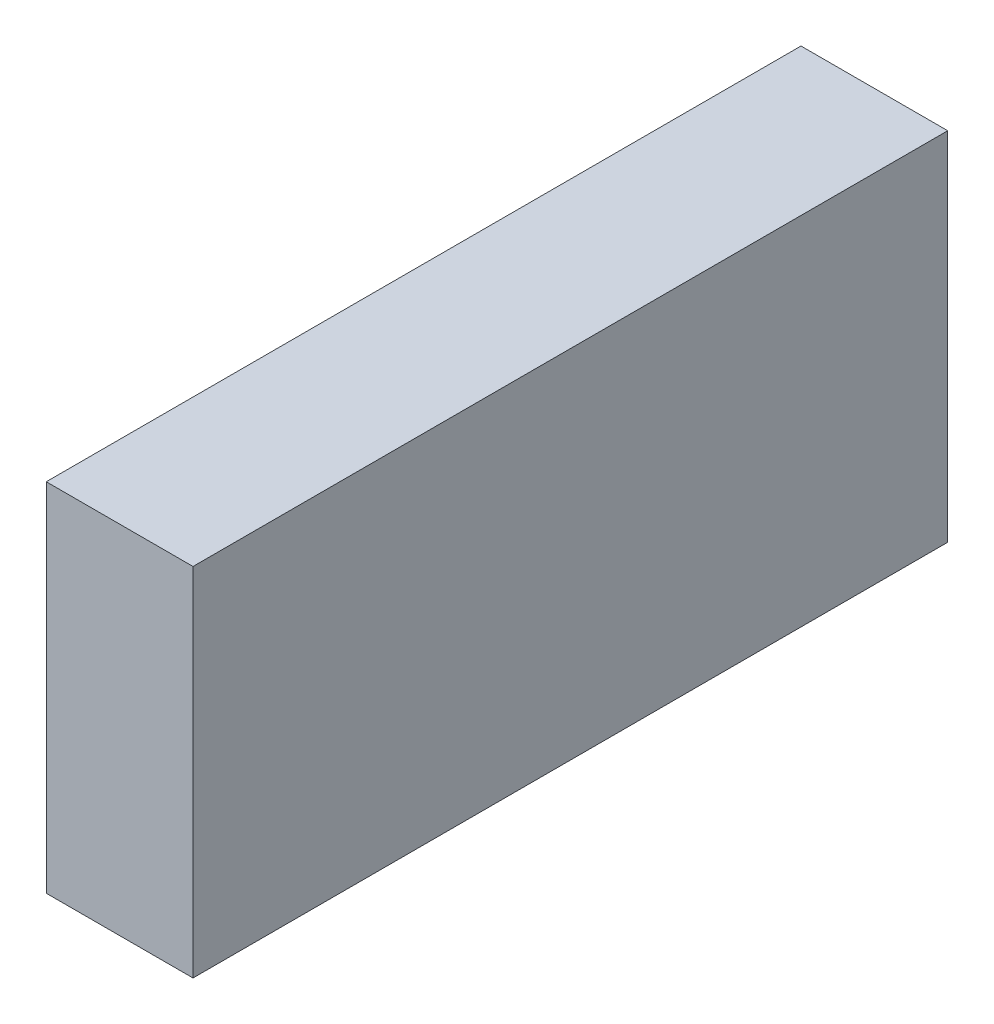
SolidWorks part; units mm, degrees
ref_plane "Front Plane" through (0, 0, 0) normal (0, 0, 1) x (1, 0, 0)
ref_plane "Top Plane" through (0, 0, 0) normal (0, 1, 0) x (1, 0, 0)
ref_plane "Right Plane" through (0, 0, 0) normal (1, 0, 0) x (0, 0, -1)
sketch "Sketch1" plane through (0, 0, 0) normal (1, 0, 0) x (0, 0, -1)
  line L0 (0, 30.4888) -> (0, -39.691) construction
  line L1 (-52.382, 0) -> (46.1124, 0) construction
  line L3 (36, -17) -> (-36, -17)
  line L4 (36, -17) -> (36, 17)
  line L5 (36, 17) -> (-36, 17)
  line L6 (-36, -17) -> (-36, 17)
  line L7 (36, -17) -> (-36, 17) construction
  line L8 (36, 17) -> (-36, -17) construction
  point P5 (0, 0)
  dimension "D1" = 72
  dimension "D2" = 34
extrude "Boss-Extrude1" add sketch "Sketch1" along normal mid plane 14
